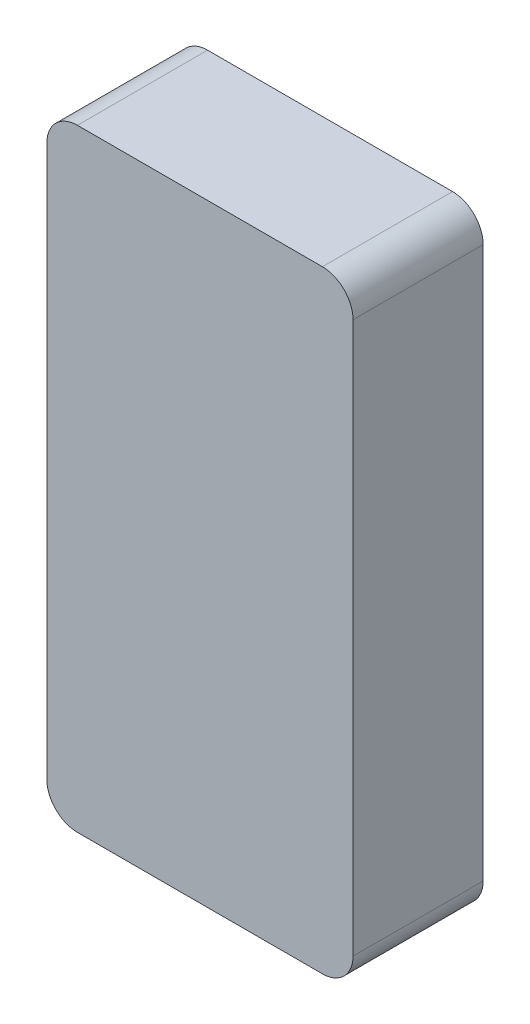
SolidWorks part; units mm, degrees
ref_plane "Front Plane" through (0, 0, 0) normal (0, 0, 1) x (1, 0, 0)
ref_plane "Top Plane" through (0, 0, 0) normal (0, 1, 0) x (1, 0, 0)
ref_plane "Right Plane" through (0, 0, 0) normal (1, 0, 0) x (0, 0, -1)
sketch "Sketch1" plane through (0, 0, 0) normal (0, 0, 1) x (1, 0, 0)
  line L1 (-10, 20) -> (10, 20)
  line L2 (-10, 20) -> (-10, -20)
  line L3 (-10, -20) -> (10, -20)
  line L4 (10, 20) -> (10, -20)
  point P4 (0, 20)
  point P6 (-10, 0)
  dimension "D1" = 20
  dimension "D2" = 40
extrude "Boss-Extrude1" add sketch "Sketch1" along normal blind 8.5
fillet "Fillet1" radius 2 4 edges at (-10, -20, 4.25) (10, -20, 4.25) (-10, 20, 4.25) (10, 20, 4.25)
